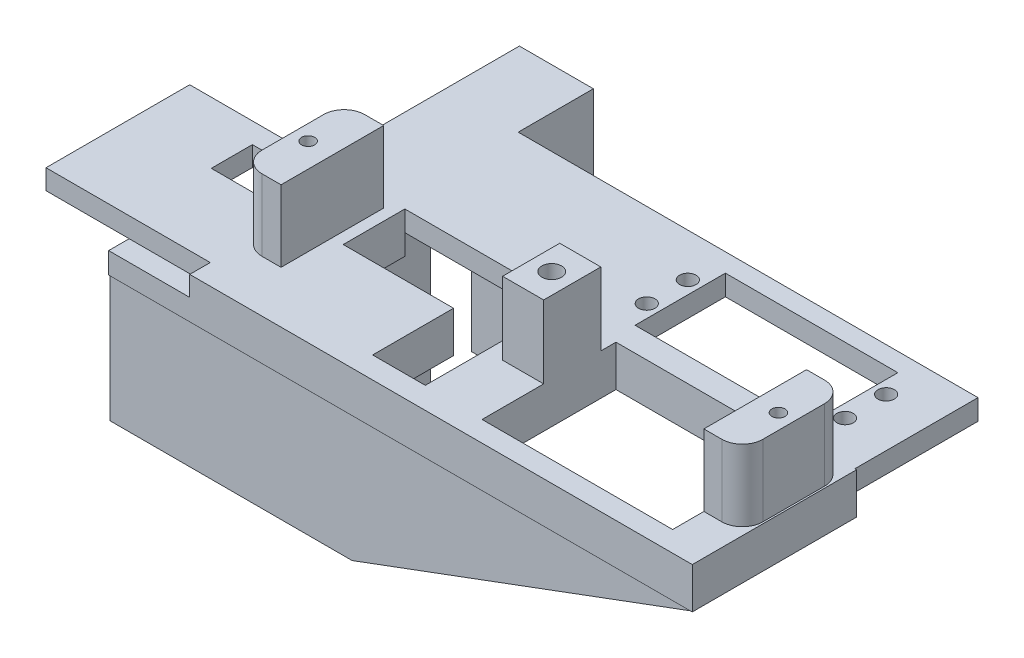
SolidWorks part; units mm, degrees
ref_plane "Front Plane" through (0, 0, 0) normal (0, 0, 1) x (1, 0, 0)
ref_plane "Top Plane" through (0, 0, 0) normal (0, 1, 0) x (1, 0, 0)
ref_plane "Right Plane" through (0, 0, 0) normal (1, 0, 0) x (0, 0, -1)
sketch "Sketch1" plane through (0, 0, 0) normal (0, 1, 0) x (1, 0, 0)
  line L1 (-60, -40) -> (60, -40)
  line L2 (-60, -40) -> (-60, 40)
  line L3 (-60, 40) -> (60, 40)
  line L4 (60, -40) -> (60, 40)
  line L5 (-60, -40) -> (60, 40) construction
  line L6 (-60, 40) -> (60, -40) construction
  point P0 (0, 0)
  dimension "D1" = 120
  dimension "D2" = 80
extrude "Boss-Extrude1" add sketch "Sketch1" along normal blind 5
sketch "Sketch2" plane through (0, 5, 0) normal (0, 1, 0) x (1, 0, 0)
  circle A0 centre (47.5, -20.5) radius 2
  circle A1 centre (47.5, -30.5) radius 2
  circle A2 centre (-0.8, -30.5) radius 2
  circle A3 centre (-0.8, -20.5) radius 2
extrude "Cut-Extrude2" cut sketch "Sketch2" against normal blind 5
sketch "Sketch3" plane through (0, 5, 0) normal (0, 1, 0) x (1, 0, 0)
  line L1 (60, 40) -> (-30, 40)
  line L2 (60, 40) -> (60, -10)
  line L3 (60, -10) -> (-30, -10)
  line L4 (-30, 40) -> (-30, -10)
  dimension "D1" = 90
  dimension "D2" = 50
extrude "Cut-Extrude3" cut sketch "Sketch3" against normal blind 5
sketch "Sketch4" plane through (0, 0, 40) normal (0, 0, 1) x (1, 0, 0)
  line L0 (-60, 0) -> (60, 0) construction
  line L1 (60, 5) -> (50, 5)
  line L2 (60, 5) -> (60, 0)
  line L3 (60, 0) -> (50, 0)
  line L4 (50, 5) -> (50, 0)
  dimension "D1" = 10
extrude "Boss-Extrude2" add sketch "Sketch4" along normal blind 27.39
sketch "Sketch5" plane through (0, 0, 40) normal (0, 0, 1) x (1, 0, 0)
  line L0 (-1.41, 5) -> (-1.41, 0)
  line L1 (-60, 5) -> (50, 5) construction
  line L2 (-60, 0) -> (50, 0) construction
  line L3 (50, 5) -> (50, 0) construction
  line L5 (-6.41, 0) -> (3.59, 0)
  line L6 (-6.41, 0) -> (-6.41, 5)
  line L7 (-6.41, 5) -> (3.59, 5)
  line L8 (3.59, 0) -> (3.59, 5)
  line L9 (-6.41, 0) -> (3.59, 5) construction
  line L10 (-6.41, 5) -> (3.59, 0) construction
  point P8 (-1.41, 2.5)
  dimension "D1" = 51.41
  dimension "D2" = 10
extrude "Boss-Extrude3" add sketch "Sketch5" along normal blind 20 contours L6 L7 L8 L5
sketch "Sketch6" plane through (0, 5, 0) normal (0, 1, 0) x (1, 0, 0)
  line L0 (-6.41, -53.04) -> (3.59, -53.04)
  line L1 (-6.41, -60) -> (-6.41, -40) construction
  line L2 (3.59, -60) -> (3.59, -40) construction
  line L3 (3.59, -40) -> (50, -40) construction
  line L5 (-6.41, -46.08) -> (3.59, -46.08)
  line L6 (-6.41, -46.08) -> (-6.41, -60)
  line L7 (-6.41, -60) -> (3.59, -60)
  line L8 (3.59, -46.08) -> (3.59, -60)
  line L9 (-6.41, -46.08) -> (3.59, -60) construction
  line L10 (-6.41, -60) -> (3.59, -46.08) construction
  circle A0 centre (-1.41, -53.04) radius 2.4
  line M12 (-6.41, -40) -> (-6.41, -60)
  line M13 (-6.41, -60) -> (3.59, -60)
  line M14 (3.59, -60) -> (3.59, -40)
  dimension "D2" = 4.8
  dimension "D1" = 13.04
extrude "Boss-Extrude4" add sketch "Sketch6" along normal blind 17.71 contours A0 L0 L5 M14 M12 | A0 L0 M12 M13 M14
sketch "Sketch7" plane through (0, 5, 0) normal (0, 1, 0) x (1, 0, 0)
  line L0 (60, -67.39) -> (60, -10) construction
  line L1 (50, -67.39) -> (60, -67.39)
  line L2 (50, -67.39) -> (50, -40)
  line L3 (50, -40) -> (60, -40)
  line L4 (60, -67.39) -> (60, -40)
  point P9 (0, 0)
extrude "Boss-Extrude5" add sketch "Sketch7" along normal blind 17.41
sketch "Sketch8" plane through (0, 22.41, 0) normal (0, 1, 0) x (1, 0, 0)
  line L0 (60, -67.39) -> (60, -40) construction
  line L1 (50, -40) -> (60, -40)
  line L2 (50, -40) -> (50, -42.39)
  line L3 (50, -42.39) -> (60, -42.39)
  line L4 (60, -40) -> (60, -42.39)
  dimension "D1" = 2.39
extrude "Cut-Extrude4" cut sketch "Sketch8" against normal blind 17.41
sketch "Sketch9" plane through (60, 0, 0) normal (1, 0, 0) x (0, 0, -1)
  line L1 (-67.39, 22.41) -> (-10, 22.41)
  line L2 (-67.39, 22.41) -> (-67.39, 0)
  line L3 (-67.39, 0) -> (-10, 0)
  line L4 (-10, 22.41) -> (-10, 0)
extrude "Cut-Extrude5" cut sketch "Sketch9" against normal blind 0.63
fillet "Fillet1" radius 5 2 edges at (59.37, 13.705, 42.39) (59.37, 11.205, 67.39)
sketch "Sketch10" plane through (0, 0, 0) normal (0, -1, 0) x (1, 0, 0)
  circle A0 centre (55.6583, 54.8853) radius 1.6
  dimension "D1" = 3.2
extrude "Cut-Extrude6" cut sketch "Sketch10" against normal through all
sketch "Sketch11" plane through (-60, 0, 0) normal (-1, 0, 0) x (0, 0, 1)
  line L1 (10, 5) -> (40, 5)
  line L2 (10, 5) -> (10, 0)
  line L3 (10, 0) -> (40, 0)
  line L4 (40, 5) -> (40, 0)
extrude "Boss-Extrude6" add sketch "Sketch11" along normal blind 2.61
sketch "Sketch12" plane through (0, 0, 40) normal (0, 0, 1) x (1, 0, 0)
  line L0 (-62.61, 0) -> (-6.41, 0) construction
  line L1 (-62.61, 5) -> (-52.98, 5)
  line L2 (-62.61, 5) -> (-62.61, 0)
  line L3 (-62.61, 0) -> (-52.98, 0)
  line L4 (-52.98, 5) -> (-52.98, 0)
  dimension "D1" = 9.63
extrude "Boss-Extrude7" add sketch "Sketch12" along normal blind 27.39
sketch "Sketch13" plane through (0, 5, 0) normal (0, 1, 0) x (1, 0, 0)
  line L0 (-62.61, -67.39) -> (-62.61, -10) construction
  line L1 (-52.98, -67.39) -> (-62.61, -67.39)
  line L2 (-52.98, -67.39) -> (-52.98, -42.39)
  line L3 (-52.98, -42.39) -> (-62.61, -42.39)
  line L4 (-62.61, -67.39) -> (-62.61, -42.39)
extrude "Boss-Extrude8" add sketch "Sketch13" along normal up to surface (17.41 mm away) up to face at (55.6583, 22.41, 53.2853)
fillet "Fillet2" radius 5 2 edges at (-62.61, 11.205, 67.39) (-62.61, 13.705, 42.39)
sketch "Sketch14" plane through (0, 0, 0) normal (0, -1, 0) x (-1, 0, 0)
  circle A0 centre (58.8926, -54.8853) radius 1.6
  dimension "D1" = 3.2
extrude "Cut-Extrude7" cut sketch "Sketch14" against normal through all
sketch "Sketch15" plane through (0, 0, 40) normal (0, 0, 1) x (1, 0, 0)
  line L0 (-6.41, 0) -> (3.59, 0) construction
  line L1 (-62.61, -5) -> (59.79, -5)
  line L2 (-62.61, -5) -> (-62.61, 5)
  line L3 (-62.61, 5) -> (59.79, 5)
  line L4 (59.79, -5) -> (59.79, 5)
  line L5 (-62.61, -5) -> (59.79, 5) construction
  line L6 (-62.61, 5) -> (59.79, -5) construction
  line L7 (3.59, 5) -> (50, 5) construction
  line L8 (-62.61, 0) -> (-62.61, 22.41) construction
  point P0 (-1.41, 0)
  point P9 (-62.61, 5)
extrude "Boss-Extrude9" add sketch "Sketch15" along normal blind 40 contours L1 L4 L3 L2
sketch "Sketch16" plane through (0, 5, 0) normal (0, 1, 0) x (1, 0, 0)
  line L1 (-60, 40) -> (-30, 40)
  line L2 (-60, 40) -> (-60, -10)
  line L3 (-60, -10) -> (-30, -10)
  line L4 (-30, 40) -> (-30, -10)
extrude "Cut-Extrude8" cut sketch "Sketch16" against normal through all
sketch "Sketch17" plane through (-62.61, 0, 0) normal (-1, 0, 0) x (0, 0, 1)
  line L0 (47.39, 5) -> (10, 5) construction
  line L1 (40, 5) -> (75.0002, 5)
  line L2 (40, 5) -> (40, 0.15)
  line L3 (40, 0.15) -> (75.0002, 0.15)
  line L4 (75.0002, 5) -> (75.0002, 0.15)
  dimension "D1" = 4.85
extrude "Boss-Extrude10" add sketch "Sketch17" along normal blind 40
sketch "Sketch18" plane through (0, 0, 40) normal (0, 0, -1) x (-1, 0, 0)
  line L0 (102.61, 0.15) -> (62.61, 0.15) construction
  line L5 (62.61, 5) -> (82.61, 5)
  line L6 (62.61, 5) -> (62.61, 0.15)
  line L7 (62.61, 0.15) -> (82.61, 0.15)
  line L8 (82.61, 5) -> (82.61, 0.15)
extrude "Boss-Extrude11" add sketch "Sketch18" along normal blind 60
sketch "Sketch19" plane through (0, 0, 10) normal (0, 0, -1) x (-1, 0, 0)
  line L0 (62.61, 5) -> (-59.37, 5) construction
  line L1 (62.61, 0.15) -> (52.61, 0.15)
  line L2 (62.61, 0.15) -> (62.61, 5)
  line L3 (62.61, 5) -> (52.61, 5)
  line L4 (52.61, 0.15) -> (52.61, 5)
  dimension "D1" = 10
extrude "Boss-Extrude12" add sketch "Sketch19" along normal up to surface (30 mm away) up to face at (-72.61, 2.575, -20)
sketch "Sketch20" plane through (0, 0.15, 0) normal (0, -1, 0) x (1, 0, 0)
  line L6 (-52.61, -20) -> (-70.63, -20)
  line L7 (-52.61, -20) -> (-52.61, 45)
  line L8 (-52.61, 45) -> (-70.63, 45)
  line L9 (-70.63, -20) -> (-70.63, 45)
  dimension "D1" = 18.02
  dimension "D2" = 65
extrude "Boss-Extrude13" add sketch "Sketch20" along normal blind 53.74
sketch "Sketch21" plane through (0, -53.59, 0) normal (0, -1, 0) x (1, 0, 0)
  circle A0 centre (-61.6171, 37.3853) radius 2.4
  circle A1 centre (-61.6171, -2.6147) radius 2.4
  dimension "D1" = 4.8
  dimension "D2" = 4.8
extrude "Cut-Extrude9" cut sketch "Sketch21" against normal blind 25
sketch "Sketch22" plane through (0, -5, 0) normal (0, -1, 0) x (1, 0, 0)
  line L1 (-26.3456, 76.7136) -> (-79.3527, 76.7136)
  line L2 (-26.3456, 76.7136) -> (-26.3456, 58.0065)
  line L3 (-26.3456, 58.0065) -> (-79.3527, 58.0065)
  line L4 (-79.3527, 76.7136) -> (-79.3527, 58.0065)
  arc A0 (-26.1992, 76.36) -> (-26.6992, 76.86) centre (-26.6992, 76.36) ccw construction
  arc A1 (-79.4992, 58.36) -> (-78.9992, 57.86) centre (-78.9992, 58.36) ccw construction
  circle A2 centre (-28.6992, 72.36) radius 2.4
  circle A3 centre (-28.6992, 62.36) radius 2.4
  circle A4 centre (-76.9992, 72.36) radius 2.4
  circle A5 centre (-76.9992, 62.36) radius 2.4
sketch "Sketch23" plane through (0, 0, 80) normal (0, 0, 1) x (1, 0, 0)
  line L0 (59.79, -5) -> (59.79, 5) construction
  line L1 (-62.61, -5) -> (59.79, -5)
  line L2 (-62.61, -5) -> (-62.61, 0)
  line L3 (-62.61, 0) -> (59.79, 0)
  line L4 (59.79, -5) -> (59.79, 0)
sketch "Sketch24" plane through (0, -5, 0) normal (0, -1, 0) x (1, 0, 0)
  line L1 (-26.3456, 76.7136) -> (-79.3527, 76.7136)
  line L2 (-26.3456, 76.7136) -> (-26.3456, 58.0065)
  line L3 (-26.3456, 58.0065) -> (-79.3527, 58.0065)
  line L4 (-79.3527, 76.7136) -> (-79.3527, 58.0065)
  arc A0 (-26.1992, 76.36) -> (-26.6992, 76.86) centre (-26.6992, 76.36) ccw construction
  arc A1 (-79.4992, 58.36) -> (-78.9992, 57.86) centre (-78.9992, 58.36) ccw construction
  circle A2 centre (-28.6992, 72.36) radius 2.4
  circle A3 centre (-28.6992, 62.36) radius 2.4
  circle A4 centre (-76.9992, 72.36) radius 2.4
  circle A5 centre (-76.9992, 62.36) radius 2.4
sketch "Sketch25" plane through (0, -5, 0) normal (0, -1, 0) x (1, 0, 0)
  line L0 (-23.3456, 79.7136) -> (-82.3527, 79.7136)
  line L1 (-82.3527, 79.7136) -> (-82.3527, 55.0065)
  line L2 (-82.3527, 55.0065) -> (-23.3456, 55.0065)
  line L3 (-23.3456, 55.0065) -> (-23.3456, 79.7136)
  line L4 (-26.3456, 76.7136) -> (-79.3527, 76.7136)
  line L5 (-79.3527, 76.7136) -> (-79.3527, 58.0065)
  line L6 (-79.3527, 58.0065) -> (-26.3456, 58.0065)
  line L7 (-26.3456, 58.0065) -> (-26.3456, 76.7136)
  line L8 (-26.3456, 76.7136) -> (-79.3527, 76.7136)
  line L9 (-79.3527, 76.7136) -> (-79.3527, 58.0065)
  line L10 (-79.3527, 58.0065) -> (-26.3456, 58.0065)
  line L11 (-26.3456, 58.0065) -> (-26.3456, 76.7136)
  circle A1 centre (-28.6992, 62.36) radius 2.4
  circle A2 centre (-28.6992, 62.36) radius 2.4
  circle A3 centre (-28.6992, 72.36) radius 2.4
  circle A4 centre (-28.6992, 72.36) radius 2.4
  circle A5 centre (-76.9992, 62.36) radius 2.4
  circle A6 centre (-76.9992, 62.36) radius 2.4
  circle A7 centre (-76.9992, 72.36) radius 2.4
  circle A8 centre (-76.9992, 72.36) radius 2.4
  line M17 (-62.61, 80) -> (-62.61, 45)
  dimension "D1" = 0
  dimension "D2" = 0
  dimension "D3" = 0
  dimension "D4" = 0
  dimension "D5" = 0
  dimension "D6" = 3
extrude "Boss-Extrude14" add sketch "Sketch25" along normal blind 30.87 contours A8 L9 L8 L0 L1 L2 L10 A6 M17 | A4 L11 A2 L10 L2 L3 L0 L8 M17 | A4 L11 L8 L10 A2 M17 | A8 L9 A6 L10 L8 M17
sketch "Sketch26" plane through (0, -35.87, 0) normal (0, -1, 0) x (1, 0, 0)
  line L10 (-74.1983, 78.7223) -> (-74.1983, 56.0025)
  line L11 (-31.5614, 56.173) -> (-74.1983, 56.0025)
  line L12 (-31.4972, 78.3514) -> (-31.5614, 56.173)
  line L13 (-31.4972, 78.3514) -> (-74.1983, 78.7223)
  point P0 (-32.5001, 77.36)
extrude "Cut-Extrude10" [suppressed] cut sketch "Sketch26" against normal blind 32
sketch "Sketch27" [suppressed] plane through (0, -35.87, 0) normal (0, -1, 0) x (1, 0, 0)
  line L5 (-74.1983, 78.7223) -> (-31.5614, 78.7223)
  line L6 (-74.1983, 78.7223) -> (-74.1983, 56.173)
  line L7 (-74.1983, 56.173) -> (-31.5614, 56.173)
  line L8 (-31.5614, 78.7223) -> (-31.5614, 56.173)
sketch "Sketch28" plane through (0, -35.87, 0) normal (0, -1, 0) x (1, 0, 0)
  line L4 (-31.5614, 78.7223) -> (-74.1983, 78.7223)
  line L5 (-31.5614, 56.173) -> (-31.5614, 78.7223)
  line L6 (-74.1983, 56.173) -> (-31.5614, 56.173)
  line L7 (-74.1983, 78.7223) -> (-74.1983, 56.173)
  line L8 (-31.5614, 78.7223) -> (-74.1983, 78.7223)
  line L9 (-31.5614, 56.173) -> (-31.5614, 78.7223)
  line L10 (-74.1983, 56.173) -> (-31.5614, 56.173)
  line L11 (-74.1983, 78.7223) -> (-74.1983, 56.173)
  dimension "D1" = 0
extrude "Cut-Extrude11" cut sketch "Sketch28" against normal blind 32
sketch "Sketch29" plane through (0, 0, -20) normal (0, 0, -1) x (-1, 0, 0)
  line L0 (82.61, 5) -> (52.61, 5) construction
  line L1 (82.61, 0.15) -> (70.63, 0.15)
  line L2 (82.61, 0.15) -> (82.61, 5)
  line L3 (82.61, 5) -> (70.63, 5)
  line L4 (70.63, 0.15) -> (70.63, 5)
extrude "Cut-Extrude12" cut sketch "Sketch29" against normal blind 60
sketch "Sketch30" plane through (-62.61, 0, 0) normal (-1, 0, 0) x (0, 0, 1)
  line L0 (56.173, -5) -> (45, -5)
  line L1 (45, -5) -> (45, 0.15)
  line L2 (45, 0.15) -> (80, 0.15)
  line L3 (80, -5) -> (80, 5) construction
  line L4 (80, 0.15) -> (80, -5)
  line L5 (80, -5) -> (78.7223, -5)
  line L9 (56.173, -5) -> (78.7223, -5)
extrude "Boss-Extrude15" add sketch "Sketch30" along normal up to surface (19.7427 mm away) up to face at (-82.3527, -20.435, 67.36)
sketch "Sketch31" plane through (0, 0, 79.7136) normal (0, 0, 1) x (1, 0, 0)
  line L0 (-23.3456, -35.87) -> (59.79, -5)
  line L1 (59.79, -5) -> (-23.3456, -5)
  line L2 (-23.3456, -5) -> (-23.3456, -35.87)
extrude "Boss-Extrude16" add sketch "Sketch31" against normal blind 5
sketch "Sketch32" plane through (0, 5, 0) normal (0, 1, 0) x (1, 0, 0)
  line L0 (2.35, -14.5) -> (2.35, -36.5)
  line L5 (2.35, -36.5) -> (44.35, -36.5)
  line L6 (44.35, -14.5) -> (44.35, -36.5)
  line L7 (2.35, -14.5) -> (44.35, -14.5)
extrude "Cut-Extrude13" cut sketch "Sketch32" against normal blind 25
sketch "Sketch33" plane through (0, -53.59, 0) normal (0, -1, 0) x (1, 0, 0)
  line L1 (-70.63, 45) -> (-70.63, -20) construction
  line L2 (-52.61, -20) -> (-52.61, 45) construction
  line L4 (-52.61, 40) -> (-52.61, 10) construction
  line L5 (-52.61, 31.3853) -> (-70.63, 31.3853)
  line L7 (-70.63, 31.3853) -> (-70.63, 3.3853)
  line L8 (-70.63, 3.3853) -> (-52.61, 3.3853)
  line L9 (-52.61, 31.3853) -> (-52.61, 3.3853)
  circle A1 centre (-61.6171, 37.3853) radius 2.4 construction
  circle A2 centre (-61.6171, -2.6147) radius 2.4 construction
  dimension "D1" = 6
  dimension "D2" = 6
extrude "Cut-Extrude14" cut sketch "Sketch33" against normal blind 50
sketch "Sketch34" plane through (0, -53.59, 0) normal (0, -1, 0) x (1, 0, 0)
  line L0 (-70.63, -8.3073) -> (-52.61, -8.3073)
  line L1 (-70.63, 3.3853) -> (-70.63, -20) construction
  line L2 (-52.61, -20) -> (-52.61, 3.3853) construction
  line L3 (-52.61, -8.3073) -> (-52.61, -20)
  line L4 (-52.61, -20) -> (-70.63, -20)
  line L5 (-70.63, -20) -> (-70.63, -8.3073)
extrude "Cut-Extrude15" cut sketch "Sketch34" against normal blind 60
sketch "Sketch35" plane through (-23.3456, 0, 0) normal (1, 0, 0) x (0, 0, -1)
  line L0 (-55.0065, -35.87) -> (-55.0065, -5) construction
  line L1 (-74.7136, -5) -> (-55.0065, -5)
  line L2 (-74.7136, -5) -> (-74.7136, -25)
  line L3 (-74.7136, -25) -> (-55.0065, -25)
  line L4 (-55.0065, -5) -> (-55.0065, -25)
  dimension "D1" = 20
extrude "Cut-Extrude16" cut sketch "Sketch35" against normal blind 60
sketch "Sketch36" plane through (0, 5, 0) normal (0, 1, 0) x (1, 0, 0)
  line L5 (-62.61, -80) -> (59.79, -80) construction
  line L6 (50, -42.39) -> (3.59, -42.39)
  line L7 (50, -42.39) -> (50, -75)
  line L8 (50, -75) -> (3.59, -75)
  line L9 (3.59, -42.39) -> (3.59, -75)
  dimension "D1" = 5
extrude "Cut-Extrude18" cut sketch "Sketch36" against normal blind 60
sketch "Sketch37" plane through (0, -5, 0) normal (0, -1, 0) x (1, 0, 0)
  line L0 (-82.3527, 45) -> (-82.3527, 55.0065)
  line L1 (-82.3527, 55.0065) -> (-23.3456, 55.0065)
  line L2 (-23.3456, 55.0065) -> (-23.3456, 74.7136)
  line L3 (-23.3456, 74.7136) -> (-10.5217, 74.7136)
  line L4 (-23.3456, 74.7136) -> (3.59, 74.7136) construction
  line L5 (-10.5217, 74.7136) -> (-10.5217, 40)
  line L6 (-52.61, 40) -> (59.79, 40) construction
  line L7 (-10.5217, 40) -> (-52.61, 40)
  line L8 (-52.61, 40) -> (-52.61, 45)
  line L9 (-52.61, 45) -> (-82.3527, 45)
extrude "Cut-Extrude19" [suppressed] cut sketch "Sketch37" against normal blind 4
sketch "Sketch38" plane through (0, 5, 0) normal (0, 1, 0) x (1, 0, 0)
  line L0 (-64.5148, -45) -> (-64.5148, -55.0065)
  line L1 (-50.2159, -40) -> (-50.2159, -55.0065)
  line L2 (-50.2159, -55.0065) -> (-23.3456, -55.0065)
  line L8 (-52.61, -40) -> (-52.61, -45)
  line L9 (-10.5217, -40) -> (-52.61, -40)
  line L10 (-10.5217, -74.7136) -> (-10.5217, -40)
  line L11 (-23.3456, -74.7136) -> (-10.5217, -74.7136)
  line L12 (-23.3456, -55.0065) -> (-23.3456, -74.7136)
  line L13 (-82.3527, -55.0065) -> (-23.3456, -55.0065)
  line L14 (-82.3527, -45) -> (-82.3527, -55.0065)
  line L15 (-52.61, -45) -> (-82.3527, -45)
  line L17 (-10.5217, -40) -> (-50.2159, -40)
  line L18 (-10.5217, -74.7136) -> (-10.5217, -40)
  line L19 (-23.3456, -74.7136) -> (-10.5217, -74.7136)
  line L20 (-23.3456, -55.0065) -> (-23.3456, -74.7136)
  line L21 (-82.3527, -55.0065) -> (-64.5148, -55.0065)
  line L22 (-82.3527, -45) -> (-82.3527, -55.0065)
  line L23 (-64.5148, -45) -> (-82.3527, -45)
  dimension "D1" = 0
extrude "Cut-Extrude20" cut sketch "Sketch38" against normal blind 49
sketch "Sketch39" plane through (0, 22.41, 0) normal (0, 1, 0) x (1, 0, 0)
  circle A0 centre (-58.8926, -54.8853) radius 1.6
  circle A1 centre (55.6583, -54.8853) radius 1.6
extrude "Cut-Extrude21" cut sketch "Sketch39" against normal blind 49
